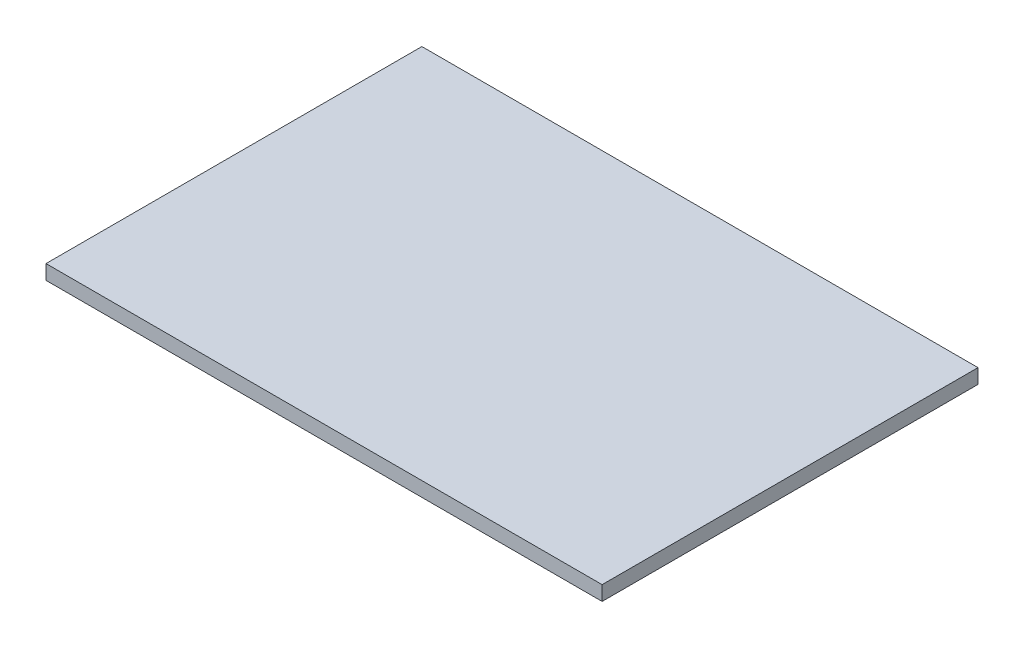
SolidWorks part; units mm, degrees
ref_plane "Front Plane" through (0, 0, 0) normal (0, 0, 1) x (1, 0, 0)
ref_plane "Top Plane" through (0, 0, 0) normal (0, 1, 0) x (1, 0, 0)
ref_plane "Right Plane" through (0, 0, 0) normal (1, 0, 0) x (0, 0, -1)
sketch "Sketch1" plane through (0, 0, 0) normal (0, 1, 0) x (1, 0, 0)
  line L1 (-45.05, 30.45) -> (45.05, 30.45)
  line L2 (-45.05, 30.45) -> (-45.05, -30.45)
  line L3 (-45.05, -30.45) -> (45.05, -30.45)
  line L4 (45.05, 30.45) -> (45.05, -30.45)
  line L5 (-45.05, 30.45) -> (45.05, -30.45) construction
  line L6 (-45.05, -30.45) -> (45.05, 30.45) construction
  point P0 (0, 0)
  dimension "D1" = 60.9
  dimension "D2" = 90.1
extrude "Boss-Extrude1" add sketch "Sketch1" along normal mid plane 2.36
